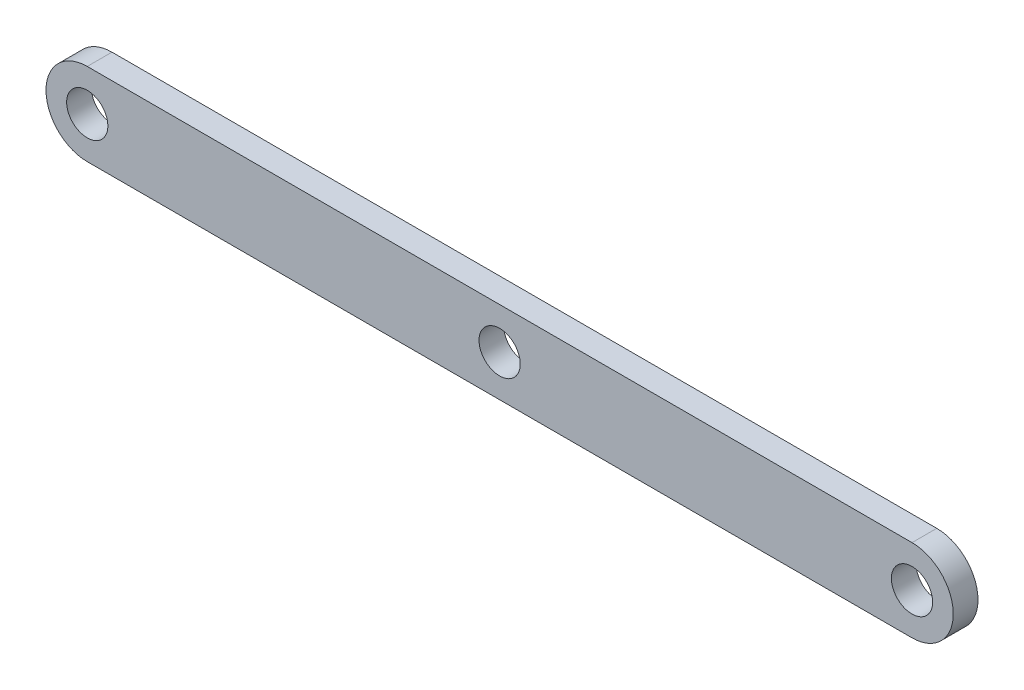
SolidWorks part; units mm, degrees
ref_plane "Front Plane" through (0, 0, 0) normal (0, 0, 1) x (1, 0, 0)
ref_plane "Top Plane" through (0, 0, 0) normal (0, 1, 0) x (1, 0, 0)
ref_plane "Right Plane" through (0, 0, 0) normal (1, 0, 0) x (0, 0, -1)
sketch "Sketch1" plane through (0, 0, 0) normal (0, 0, 1) x (1, 0, 0)
  line L0 (0, 0) -> (100, 0)
  line L1 (0, 10) -> (100, 10)
  arc A0 (100, 10) -> (100, 0) centre (100, 5) cw
  arc A1 (0, 10) -> (0, 0) centre (0, 5) ccw
  dimension "D1" = 100
  dimension "D2" = 10
extrude "Boss-Extrude1" add sketch "Sketch1" along normal blind 3
sketch "Sketch2" plane through (0, 0, 3) normal (0, 0, 1) x (1, 0, 0)
  line L0 (0, 0) -> (0, 10) construction
  line L1 (100, 0) -> (100, 10) construction
  line L2 (100, 10) -> (0, 10) construction
  line L3 (100, 5) -> (-2.967, 5) construction
  arc A0 (100, 0) -> (100, 10) centre (100, 5) ccw construction
  circle A1 centre (0, 5) radius 2.5
  circle A2 centre (100, 5) radius 2.5
  dimension "D1" = 5
  dimension "D2" = 5
extrude "Cut-Extrude1" cut sketch "Sketch2" against normal through all
sketch "Sketch3" plane through (0, 0, 3) normal (0, 0, 1) x (1, 0, 0)
  line L0 (50, 0) -> (50, 10) construction
  line L1 (0, 0) -> (100, 0) construction
  line L2 (100, 10) -> (0, 10) construction
  circle A0 centre (50, 5) radius 2.5
  dimension "D1" = 5
extrude "Cut-Extrude2" cut sketch "Sketch3" against normal blind 3
